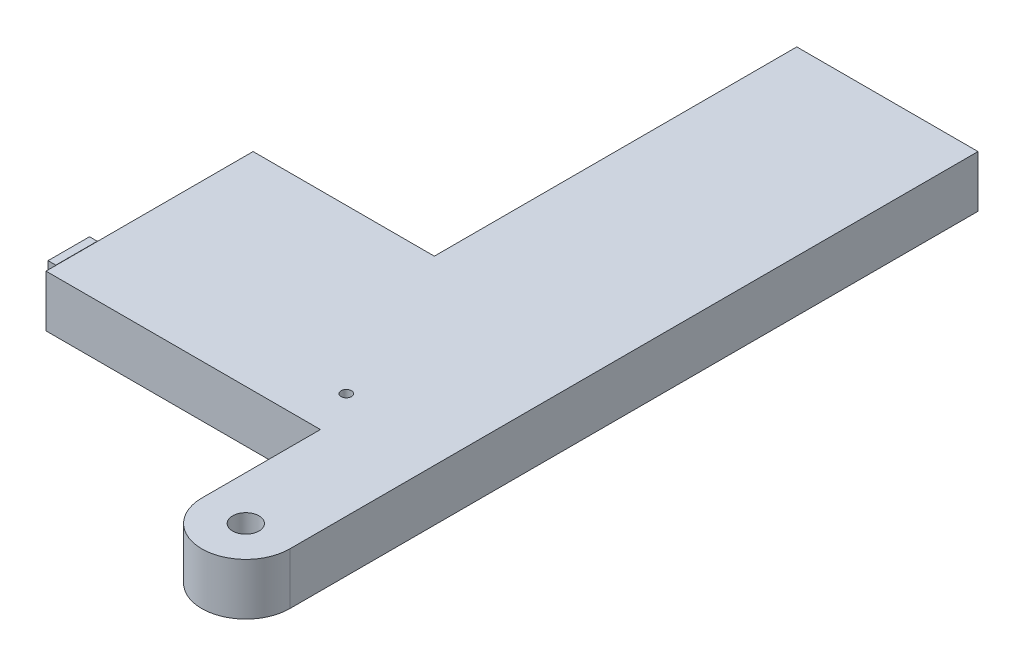
SolidWorks part; units mm, degrees
ref_plane "Front Plane" through (0, 0, 0) normal (0, 0, 1) x (1, 0, 0)
ref_plane "Top Plane" through (0, 0, 0) normal (0, 1, 0) x (1, 0, 0)
ref_plane "Right Plane" through (0, 0, 0) normal (1, 0, 0) x (0, 0, -1)
sketch "CornerrSketch1" plane through (0, 0, 0) normal (0, 1, 0) x (1, 0, 0)
  line L0 (0, 0) -> (0, 80)
  line L5 (0, 80) -> (70, 80)
  line L6 (70, 80) -> (70, 220)
  line L7 (140, 220) -> (70, 220)
  line L8 (106, -45.825) -> (106, 0)
  line L9 (0, 0) -> (106, 0)
  line L10 (140, 220) -> (140, -45.825)
  arc A0 (106, -45.825) -> (140, -45.825) centre (123, -45.825) ccw
  dimension "D5" = 34
  dimension "D4" = 80
  dimension "D3" = 70
  dimension "D1" = 220
  dimension "D2" = 45.825
  dimension "D6" = 140
extrude "CornerBoss-Extrude1" add sketch "CornerrSketch1" along normal blind 20
shell "Shell1" thickness 3
sketch "PadSketch1" plane through (0, 17, 0) normal (0, -1, 0) x (1, 0, 0)
  line L1 (0, 0) -> (106, 0) construction
  line L2 (140, 45.825) -> (140, -220) construction
  circle A0 centre (99, -17) radius 5
  circle A1 centre (123, 45.825) radius 12
  dimension "D1" = 10
  dimension "D4" = 24
  dimension "D3" = 17
  dimension "D2" = 41
extrude "PadBoss-Extrude1" add sketch "PadSketch1" along normal blind 10
sketch "StepperShaftCut-Sketch3" plane through (0, 7, 0) normal (0, -1, 0) x (1, 0, 0)
  circle A0 centre (123, 45.825) radius 5.1
  circle A1 centre (99, -17) radius 2
  dimension "D1" = 10.2
  dimension "D2" = 4
extrude "StepperShaftCut-Extrude1" cut sketch "StepperShaftCut-Sketch3" against normal through all
sketch "ThreadedNutMountHolesSketch5" plane through (0, 7, 0) normal (0, -1, 0) x (1, 0, 0)
  circle A0 centre (123, 53.825) radius 2
  circle A1 centre (131, 45.825) radius 2
  circle A2 centre (115, 45.825) radius 2
  circle A3 centre (123, 37.825) radius 2
  dimension "D3" = 4
  dimension "D1" = 8
  dimension "D2" = 16
  dimension "D4" = 8
  dimension "D5" = 16
extrude "ThreadedNutMountHolesCut-Extrude2" cut sketch "ThreadedNutMountHolesSketch5" against normal blind 10
sketch "TopPegHoleSketch4" plane through (0, 0, -220) normal (0, 0, -1) x (-1, 0, 0)
  line L1 (-130, 14) -> (-120, 14)
  line L2 (-130, 14) -> (-130, 0)
  line L3 (-130, 0) -> (-120, 0)
  line L4 (-120, 14) -> (-120, 0)
  line L5 (-140, 0) -> (-70, 0) construction
  line L6 (-140, 20) -> (-140, 0) construction
  dimension "D2" = 10
  dimension "D3" = 14
  dimension "D1" = 10
extrude "TopPegHoleCut-Extrude2" cut sketch "TopPegHoleSketch4" against normal blind 3
sketch "BLPegSketch5" plane through (0, 0, 0) normal (-1, 0, 0) x (0, 0, 1)
  line L1 (-19.9, 13.9) -> (-10.1, 13.9)
  line L2 (-19.9, 13.9) -> (-19.9, 0)
  line L3 (-19.9, 0) -> (-10.1, 0)
  line L4 (-10.1, 13.9) -> (-10.1, 0)
  line L5 (-80, 0) -> (0, 0) construction
  line L6 (0, 20) -> (0, 0) construction
  dimension "D2" = 13.9
  dimension "D3" = 9.8
  dimension "D1" = 10.1
extrude "BLPegBoss-Extrude3" add sketch "BLPegSketch5" along normal blind 3.1
sketch "BLPegCapSketch6" plane through (-3.1, 0, 0) normal (-1, 0, 0) x (0, 0, 1)
  line L0 (-19.9, 13.9) -> (-19.9, 0) construction
  line L1 (-22.9, 17) -> (-6.9, 17)
  line L2 (-22.9, 17) -> (-22.9, 0)
  line L3 (-22.9, 0) -> (-6.9, 0)
  line L4 (-6.9, 17) -> (-6.9, 0)
  line L8 (-19.9, 0) -> (-10.1, 0) construction
  dimension "D1" = 16
  dimension "D3" = 17
  dimension "D2" = 3
extrude "BLPegCapBoss-Extrude4" add sketch "BLPegCapSketch6" along normal blind 3
sketch "BedCenterPegHoleCutSketch1" plane through (70, 0, 0) normal (-1, 0, 0) x (0, 0, 1)
  line L0 (-220, 0) -> (-80, 0) construction
  line L1 (-190, 14) -> (-180, 14)
  line L2 (-190, 14) -> (-190, 0)
  line L3 (-190, 0) -> (-180, 0)
  line L4 (-180, 14) -> (-180, 0)
  line L5 (-80, 20) -> (-80, 0) construction
  dimension "D2" = 10
  dimension "D1" = 14
  dimension "D3" = 100
extrude "BedCenterPegHoleCut-Extrude1" cut sketch "BedCenterPegHoleCutSketch1" against normal blind 3
equation "\"BedThickness\"= 20mm"
equation "\"BedToBuildPlateStandoffHolesDistanceFromLeftOrRight\"= \"BuildPlateStandoffHolesDistanceFromLeftOrRight\" + \"BedIncreasedByWidth\" / 2'Equals 17"
equation "\"BedLLongSide\"= \"BedThirdSize\" * 3'Equals 210"
equation "\"BedLShortSide\"= \"BedThirdSize\" * 2'Equals 140"
equation "\"BedLWidth\"= \"BedThirdSize\"'Equals 70"
equation "\"D4@CornerrSketch1\"=\"BedLWidth\" + \"BedIncreasedByWidth\"/2"
equation "\"BedIncreasedByWidth\"= 20mm"
equation "\"BedIncreasedByLength\"= 0mm"
equation "\"BedThirdSize\"= 70mm"
equation "\"StandardWallThickness\"= 3mm"
equation "\"D2@TopPegHoleSketch4\"=\"BedPegHoleWidth\""
equation "\"D3@TopPegHoleSketch4\"=\"BedPegHoleHeight\""
equation "\"D1@TopPegHoleCut-Extrude2\" = \"StandardWallThickness\""
equation "\"D3@BLPegSketch5\"=\"BedPegWidth\""
equation "\"D1@BLPegBoss-Extrude3\"=\"BedPegBoss\""
equation "\"D2@BLPegSketch5\"=\"BedPegHeight\""
equation "\"D2@BLPegCapSketch6\"=\"StandardWallThickness\""
equation "\"D3@BLPegCapSketch6\"=\"BedPegCapHeight\""
equation "\"D1@BLPegCapBoss-Extrude4\" = \"StandardWallThickness\""
equation "\"D3@CornerrSketch1\"=\"BedLWidth\" "
equation "\"D1@PadSketch1\" = \"BedToBuildPlateStandoffPadSize\""
equation "\"D1@PadBoss-Extrude1\"=\"LeadScrewNutPadDepth\""
equation "\"BedToBuildPlateStandoffPadSize\"= 10mm"
equation "\"BedToBuildPlateStandoffHolesDistanceFromBack\"= \"BuildPlateStandoffHolesDistanceFromBack\" + \"BedIncreasedByLength\" / 2'Equals 41"
equation "\"BuildPlateStandoffHolesDistanceFromLeftOrRight\"= 7mm"
equation "\"BuildPlateStandoffHolesDistanceFromBack\"= 41mm"
equation "\"DistanceFromBedSideToStepperHole\"= ( \"DistanceBetweenLeftToRightStepperHoles\" - \"BedWidth\" ) / 2'Equals 45.825"
equation "\"DistanceBetweenLeftToRightStepperHoles\"= \"FrontBackRailLength\" - \"StepperMountingHoleOffsetFromLeftOrRightSide\" * 2 - \"StepperMountingHoleDistance\"'Equals 461.65"
equation "\"FrontBackRailLength\"= 510mm"
equation "\"StepperMountingHoleOffsetFromLeftOrRightSide\"= \"StepperMountingHoleOffsetFromItsSide\" + \"RailThickness\""
equation "\"StepperMountingHoleDistance\"= 31mm'Spec"
equation "\"StepperMountingHoleOffsetFromItsSide\"= 5.5mm'Spec"
equation "\"RailThickness\"= .125in'Spec"
equation "\"BedWidth\"= \"BedInnerSquareWidth\" + \"BedLWidth\" * 2 + \"BedIncreasedByWidth\"'Equals 370"
equation "\"BedInnerSquareWidth\"= \"BedThirdSize\" * 3'Equals 210"
equation "\"D1@CornerrSketch1\"=\"BedLLongSide\"  + \"BedIncreasedByWidth\"/2"
equation "\"D2@CornerrSketch1\"=\"DistanceFromBedSideToStepperHole\""
equation "\"D3@PadSketch1\"=\"BedToBuildPlateStandoffHolesDistanceFromLeftOrRight\""
equation "\"D2@PadSketch1\"=\"BedToBuildPlateStandoffHolesDistanceFromBack\""
equation "\"D1@TopPegHoleSketch4\"=\"BedTopPegOffsetFromSide\""
equation "\"D1@BLPegSketch5\"=\"BedTopPegOffsetFromSide\" + .1mm"
equation "\"D6@CornerrSketch1\"=\"BedLShortSide\" + \"BedIncreasedByLength\"/2"
equation "\"LeadScrewNutPadSize\"= \"LeadScrewNutMountingHoleFlangeDiameter\" + 2mm'Equals 24"
equation "\"D4@PadSketch1\"=\"LeadScrewNutPadSize\""
equation "\"D1@StepperShaftCut-Sketch3\"=\"LeadScrewNutInnerShaftFlangeDiameter\""
equation "\"D2@StepperShaftCut-Sketch3\"=\"M3HeatInsertHoleDiameter\""
equation "\"LeadScrewNutInnerShaftFlangeDiameter\"= 10.2mm'Spec"
equation "\"LeadScrewNutMountHoleDiameter\" = \"M3HeatInsertHoleDiameter\"'Spec is 4.1 but smaller for tapping"
equation "\"LeadScrewNutMountingHoleFlangeDiameter\"= 22mm'Spec"
equation "\"LeadScrewNutMountingHoleDistance\"= 16mm'Spec"
equation "\"D1@ThreadedNutMountHolesSketch5\"=\"LeadScrewNutMountingHoleDistance\"/2"
equation "\"D2@ThreadedNutMountHolesSketch5\"=\"LeadScrewNutMountingHoleDistance\""
equation "\"D4@ThreadedNutMountHolesSketch5\"=\"LeadScrewNutMountingHoleDistance\"/2"
equation "\"D5@ThreadedNutMountHolesSketch5\"=\"LeadScrewNutMountingHoleDistance\""
equation "\"D3@ThreadedNutMountHolesSketch5\"=\"LeadScrewNutMountHoleDiameter\""
equation "\"LeadScrewNutPadDepth\"= \"BedThickness\" / 2'Equals 10"
equation "\"D1@ThreadedNutMountHolesCut-Extrude2\"= \"LeadScrewNutPadDepth\""
equation "\"BedPegHoleWidth\"= 10mm"
equation "\"BedPegHoleHeight\"= \"BedThickness\" - \"StandardWallThickness\" * 2'Equals 14"
equation "\"BedPegWidth\"= \"BedPegHoleWidth\" - .1mm * 2'For easier assembly"
equation "\"BedPegHeight\"= \"BedPegHoleHeight\" - .1mm'For easier assembly"
equation "\"BedTopPegOffsetFromSide\"= 10mm"
equation "\"BedPegBoss\"= \"StandardWallThickness\" + .1mm'For easier assembly"
equation "\"BedPegCapHeight\"= \"BedThickness\" - \"StandardWallThickness\"'Equals 17"
equation "\"BedPegCapWidth\"= \"BedThickness\" / 2 + \"StandardWallThickness\" * 2'Equals 16"
equation "\"D1@BLPegCapSketch6\"=\"BedPegCapWidth\""
equation "\"D1@BedCenterPegHoleCutSketch1\" = \"BedPegHoleHeight\""
equation "\"D3@BedCenterPegHoleCutSketch1\" = \"BedInnerSquareWidth\" / 2 - \"BedPegHoleWidth\" / 2"
equation "\"D2@BedCenterPegHoleCutSketch1\" = \"BedPegHoleWidth\""
equation "\"D1@BedCenterPegHoleCut-Extrude1\"=\"StandardWallThickness\""
equation "\"M3HeatInsertHoleDiameter\"= 4mm'Spec"
